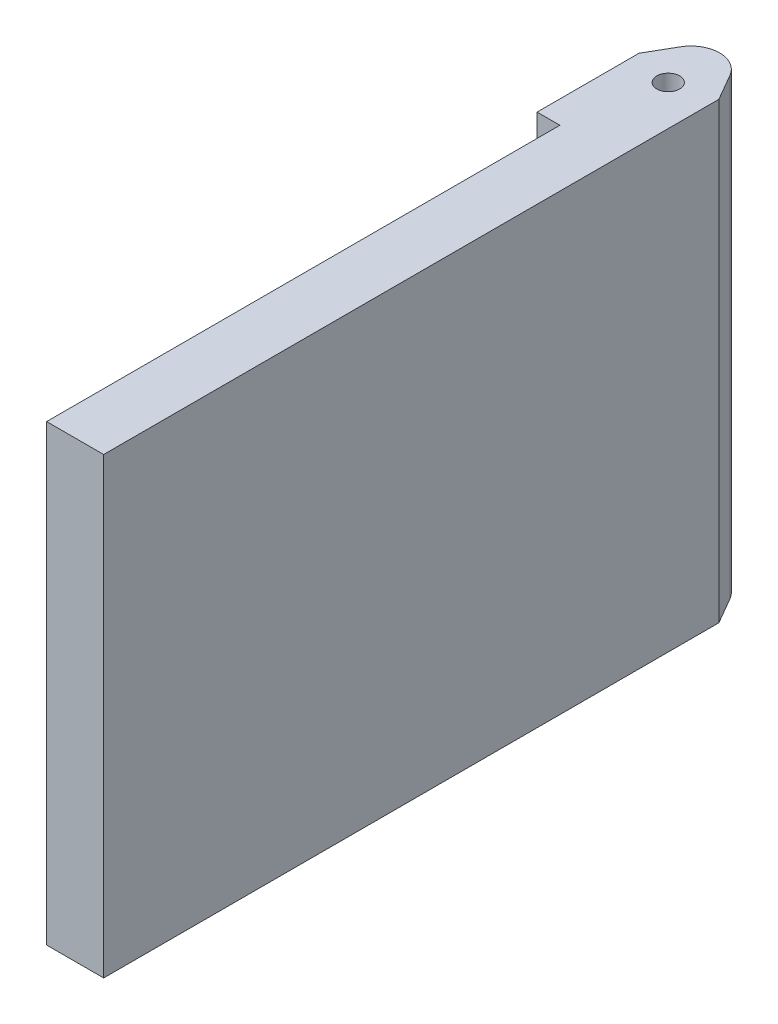
SolidWorks part; units mm, degrees
ref_plane "Front Plane" through (0, 0, 0) normal (0, 0, 1) x (1, 0, 0)
ref_plane "Top Plane" through (0, 0, 0) normal (0, 1, 0) x (1, 0, 0)
ref_plane "Right Plane" through (0, 0, 0) normal (1, 0, 0) x (0, 0, -1)
sketch "Sketch1" plane through (0, 0, 0) normal (0, 1, 0) x (1, 0, 0)
  line L1 (-15, -60) -> (15, -60)
  line L2 (-15, -60) -> (-15, 60)
  line L3 (-15, 60) -> (15, 60)
  line L4 (15, -60) -> (15, 60)
  line L5 (-15, -60) -> (15, 60) construction
  line L6 (-15, 60) -> (15, -60) construction
  point P0 (0, 0)
  dimension "D1" = 30
  dimension "D2" = 120
extrude "Boss-Extrude1" add sketch "Sketch1" along normal blind 79.5
sketch "Sketch2" plane through (0, 79.5, 0) normal (0, 1, 0) x (1, 0, 0)
  line L0 (0, 60) -> (-15, 34.0192)
  line L1 (15, 60) -> (-15, 60) construction
  line L2 (-15, 60) -> (-15, -60) construction
  line L3 (-15, 34.0192) -> (-15, -60)
  line L4 (-15, -60) -> (15, -60)
  line L5 (15, -60) -> (15, 34.0192)
  line L6 (15, -60) -> (15, 60) construction
  line L7 (15, 34.0192) -> (0, 60)
  dimension "D1" = 60
  dimension "D2" = 0
extrude "Cut-Extrude2" cut sketch "Sketch2" against normal through all flip side to cut
fillet "Fillet1" radius 5 1 edges at (0, 39.75, -60)
sketch "Sketch3" plane through (0, 79.5, 0) normal (0, 1, 0) x (1, 0, 0)
  line L0 (-15, 34.0192) -> (-15, -60)
  line L1 (-15, -60) -> (-7, -60)
  line L2 (-15, -60) -> (15, -60) construction
  line L3 (-7, -60) -> (-7, 47.8756)
  line L4 (-4.3301, 52.5) -> (-15, 34.0192) construction
  line L5 (-7, 47.8756) -> (-15, 34.0192)
  line L6 (7, 47.8756) -> (7, -60)
  line L7 (15, 34.0192) -> (4.3301, 52.5) construction
  line L8 (7, -60) -> (15, -60)
  line L9 (15, -60) -> (15, 34.0192)
  line L10 (15, 34.0192) -> (7, 47.8756)
  dimension "D1" = 8
  dimension "D2" = 8
extrude "Cut-Extrude3" cut sketch "Sketch3" against normal through all
sketch "Sketch4" plane through (0, 79.5, 0) normal (0, 1, 0) x (1, 0, 0)
  line L0 (-7, -60) -> (-7, 47.8756) construction
  line L1 (-7, 30) -> (-3, 30)
  line L2 (-7, 30) -> (-7, -60)
  line L3 (-7, -60) -> (-3, -60)
  line L4 (-3, 30) -> (-3, -60)
  line L5 (-7, -60) -> (7, -60) construction
  dimension "D1" = 90
  dimension "D2" = 4
extrude "Cut-Extrude4" cut sketch "Sketch4" against normal through all
sketch "Sketch5" plane through (0, 79.5, 0) normal (0, 1, 0) x (1, 0, 0)
  circle A0 centre (0, 46) radius 2
  arc A1 (4.3301, 52.5) -> (-4.3301, 52.5) centre (0, 50) ccw construction
  dimension "D1" = 4
extrude "Cut-Extrude5" cut sketch "Sketch5" against normal through all
